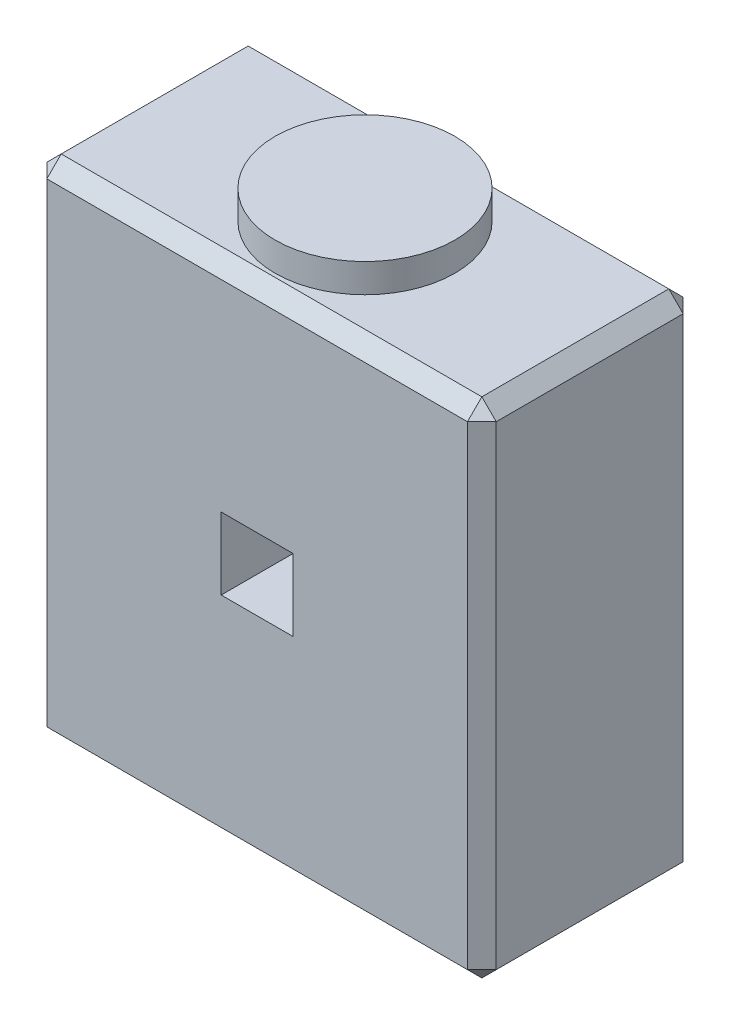
SolidWorks part; units mm, degrees
ref_plane "Front Plane" through (0, 0, 0) normal (0, 0, 1) x (1, 0, 0)
ref_plane "Top Plane" through (0, 0, 0) normal (0, 1, 0) x (1, 0, 0)
ref_plane "Right Plane" through (0, 0, 0) normal (1, 0, 0) x (0, 0, -1)
sketch "Sketch1" plane through (0, 0, 0) normal (0, 0, 1) x (1, 0, 0)
  line L1 (31.25, 35) -> (-31.25, 35)
  line L2 (31.25, 35) -> (31.25, -35)
  line L3 (31.25, -35) -> (-31.25, -35)
  line L4 (-31.25, 35) -> (-31.25, -35)
  line L5 (31.25, 35) -> (-31.25, -35) construction
  line L6 (31.25, -35) -> (-31.25, 35) construction
  point P0 (0, 0)
  dimension "D1" = 70
  dimension "D2" = 62.5
extrude "Boss-Extrude1" add sketch "Sketch1" along normal mid plane 30
sketch "Sketch2" plane through (0, 35, 0) normal (0, 1, 0) x (1, 0, 0)
  circle A0 centre (0, 0) radius 12.5
  dimension "D1" = 25
extrude "Boss-Extrude2" add sketch "Sketch2" along normal mid plane 8
chamfer "Chamfer1" distance 2 angle 45 12 edges at (-31.25, -35, 0) (31.25, -35, 0) (31.25, 35, 0) (0, 35, 15) (31.25, 0, 15) (0, -35, 15) (-31.25, 0, 15) (-31.25, 35, 0) (0, 35, -15) (31.25, 0, -15) (0, -35, -15) (-31.25, 0, -15)
sketch "Sketch3" plane through (0, 0, -15) normal (0, 0, -1) x (-1, 0, 0)
  line L0 (29.25, 33) -> (-29.25, 33) construction
  line L1 (-29.25, 33) -> (-29.25, -33) construction
  line L2 (29.25, -33) -> (29.25, 33) construction
  line L3 (-29.25, -33) -> (29.25, -33) construction
  circle A0 centre (-24.25, 28) radius 1
  circle A1 centre (24.25, 28) radius 1
  circle A2 centre (-24.25, -28) radius 1
  circle A3 centre (24.25, -28) radius 1
  dimension "D3" = 2
  dimension "D1" = 5
  dimension "D2" = 5
  dimension "D5" = 5
  dimension "D7" = 5
  dimension "D4" = 2
  dimension "D6" = 2
extrude "Cut-Extrude1" cut sketch "Sketch3" against normal blind 10
sketch "Sketch4" plane through (0, 0, 15) normal (0, 0, 1) x (1, 0, 0)
  line L1 (5, 5) -> (-5, 5)
  line L2 (5, 5) -> (5, -5)
  line L3 (5, -5) -> (-5, -5)
  line L4 (-5, 5) -> (-5, -5)
  line L5 (5, 5) -> (-5, -5) construction
  line L6 (5, -5) -> (-5, 5) construction
  point P0 (0, 0)
  dimension "D1" = 10
  dimension "D2" = 10
extrude "Cut-Extrude2" cut sketch "Sketch4" against normal blind 10
sketch "Sketch5" plane through (0, 0, -15) normal (0, 0, -1) x (-1, 0, 0)
  line L0 (1, 5) -> (10, 5)
  line L1 (-10, 5) -> (-1, 5)
  line L2 (-10, 5) -> (-10, -5)
  line L3 (-10, -5) -> (-1, -5)
  line L4 (10, 5) -> (10, -5)
  line L5 (-10, 5) -> (10, -5) construction
  line L6 (-10, -5) -> (10, 5) construction
  line L8 (-1, 5) -> (-1, -5)
  line L10 (1, 5) -> (1, -5)
  line L11 (-1, 5) -> (1, -5) construction
  line L12 (-1, -5) -> (1, 5) construction
  line L13 (1, -5) -> (10, -5)
  point P0 (0, 0)
  point P6 (0, 0)
  dimension "D1" = 10
  dimension "D2" = 20
  dimension "D3" = 2
extrude "Cut-Extrude3" cut sketch "Sketch5" against normal blind 10
